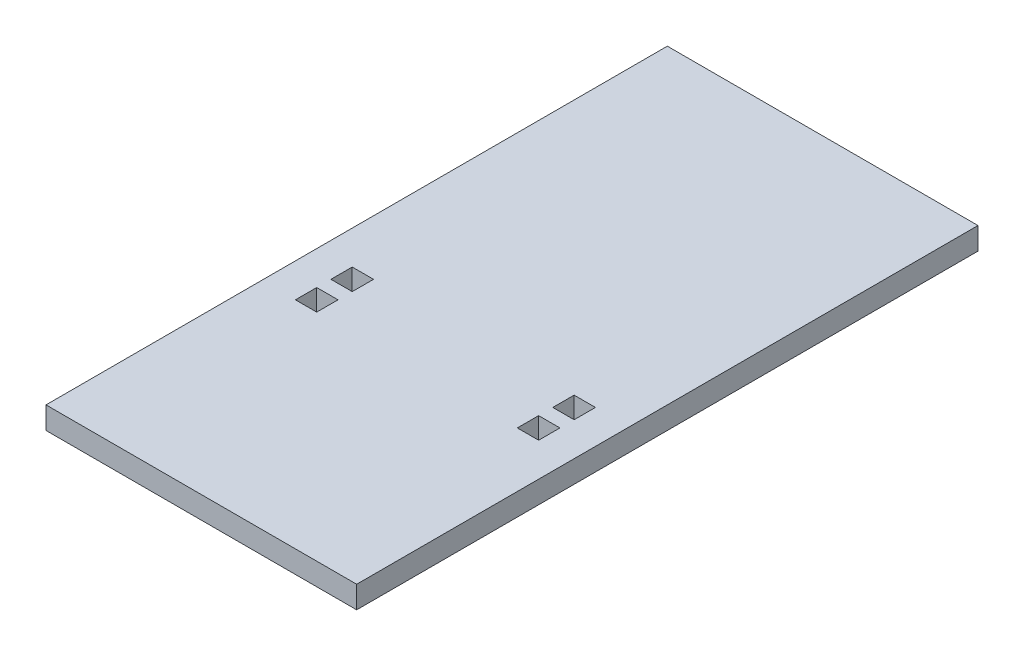
SolidWorks part; units mm, degrees
ref_plane "Front Plane" through (0, 0, 0) normal (0, 0, 1) x (1, 0, 0)
ref_plane "Top Plane" through (0, 0, 0) normal (0, 1, 0) x (1, 0, 0)
ref_plane "Right Plane" through (0, 0, 0) normal (1, 0, 0) x (0, 0, -1)
sketch "Sketch1" plane through (0, 0, 0) normal (0, 1, 0) x (1, 0, 0)
  line L0 (0, -70) -> (0, 0) construction
  line L1 (35, 70) -> (-35, 70)
  line L2 (35, 70) -> (35, -70)
  line L3 (35, -70) -> (-35, -70)
  line L4 (-35, 70) -> (-35, -70)
  line L5 (35, 70) -> (-35, -70) construction
  line L6 (35, -70) -> (-35, 70) construction
  line L7 (-27.4, -21.4) -> (-22.6, -21.4)
  line L8 (-27.4, -21.4) -> (-27.4, -16.6)
  line L9 (-27.4, -16.6) -> (-22.6, -16.6)
  line L10 (-22.6, -21.4) -> (-22.6, -16.6)
  line L11 (-27.4, -21.4) -> (-22.6, -16.6) construction
  line L12 (-27.4, -16.6) -> (-22.6, -21.4) construction
  line L13 (35, -14) -> (35, -16) construction
  line L14 (66.5154, -14) -> (-68.4846, -14) construction
  line L15 (-68.4846, -16) -> (66.5154, -16) construction
  line L16 (35, -16) -> (-35, -16) construction
  line L17 (-35, -16) -> (-35, -14) construction
  line L18 (-35, -14) -> (35, -14) construction
  line L19 (-35, -14) -> (-35, -16) construction
  line L20 (35, -16) -> (35, -14) construction
  line L21 (35, -15) -> (-35, -15) construction
  line L22 (-27.4, -13.4) -> (-22.6, -13.4)
  line L23 (-27.4, -8.6) -> (-27.4, -13.4)
  line L24 (-27.4, -8.6) -> (-22.6, -8.6)
  line L25 (-22.6, -8.6) -> (-22.6, -13.4)
  line L26 (22.6, -8.6) -> (22.6, -13.4)
  line L27 (27.4, -8.6) -> (22.6, -8.6)
  line L28 (27.4, -8.6) -> (27.4, -13.4)
  line L29 (27.4, -13.4) -> (22.6, -13.4)
  line L30 (27.4, -16.6) -> (22.6, -21.4) construction
  line L31 (27.4, -21.4) -> (22.6, -16.6) construction
  line L32 (22.6, -21.4) -> (22.6, -16.6)
  line L33 (27.4, -16.6) -> (22.6, -16.6)
  line L34 (27.4, -21.4) -> (27.4, -16.6)
  line L35 (27.4, -21.4) -> (22.6, -21.4)
  point P0 (0, 0)
  point P5 (-25, -19)
  point P35 (25, -19)
  dimension "D1" = 140
  dimension "D2" = 70
  dimension "D3" = 4.8
  dimension "D4" = 4.8
  dimension "D5" = 10
  dimension "D6" = 4
extrude "Boss-Extrude1" add sketch "Sketch1" along normal blind 5
